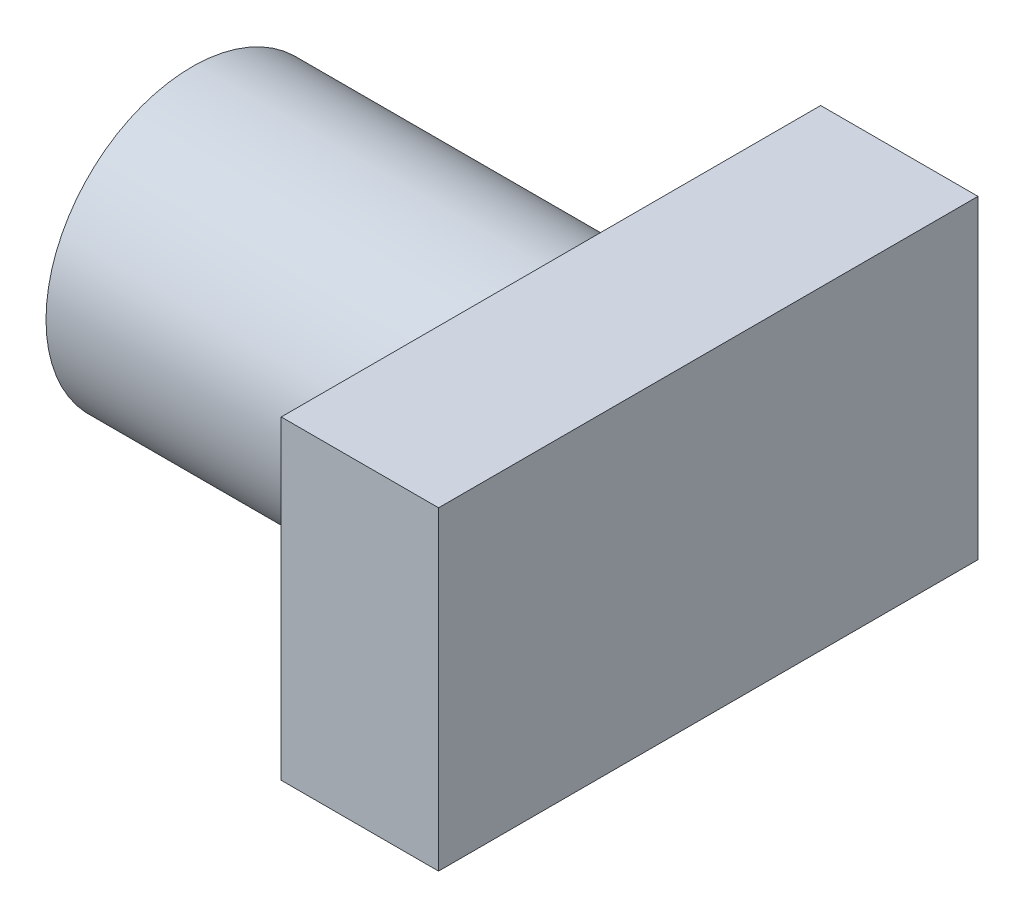
SolidWorks part; units mm, degrees
ref_plane "Front Plane" through (0, 0, 0) normal (0, 0, 1) x (1, 0, 0)
ref_plane "Top Plane" through (0, 0, 0) normal (0, 1, 0) x (1, 0, 0)
ref_plane "Right Plane" through (0, 0, 0) normal (1, 0, 0) x (0, 0, -1)
sketch "Sketch1" plane through (0, 0, 0) normal (0, 1, 0) x (1, 0, 0)
  line L1 (0, 0) -> (35, 0)
  line L2 (0, 0) -> (0, 120)
  line L3 (0, 120) -> (35, 120)
  line L4 (35, 0) -> (35, 120)
  dimension "D1" = 120
  dimension "D2" = 35
extrude "Boss-Extrude1" add sketch "Sketch1" along normal blind 70 contours L4 L3 L2 L1
sketch "Sketch2" plane through (0, 0, 0) normal (-1, 0, 0) x (0, 0, 1)
  circle A0 centre (-60.1749, 34.8908) radius 32.5
  dimension "D1" = 65
extrude "Boss-Extrude2" add sketch "Sketch2" along normal blind 80
sketch "Sketch3" plane through (0, 0, 0) normal (0, -1, 0) x (1, 0, 0)
  circle A0 centre (17.4329, -60.6234) radius 3.175
  dimension "D1" = 6.35
extrude "Cut-Extrude1" cut sketch "Sketch3" against normal blind 10
